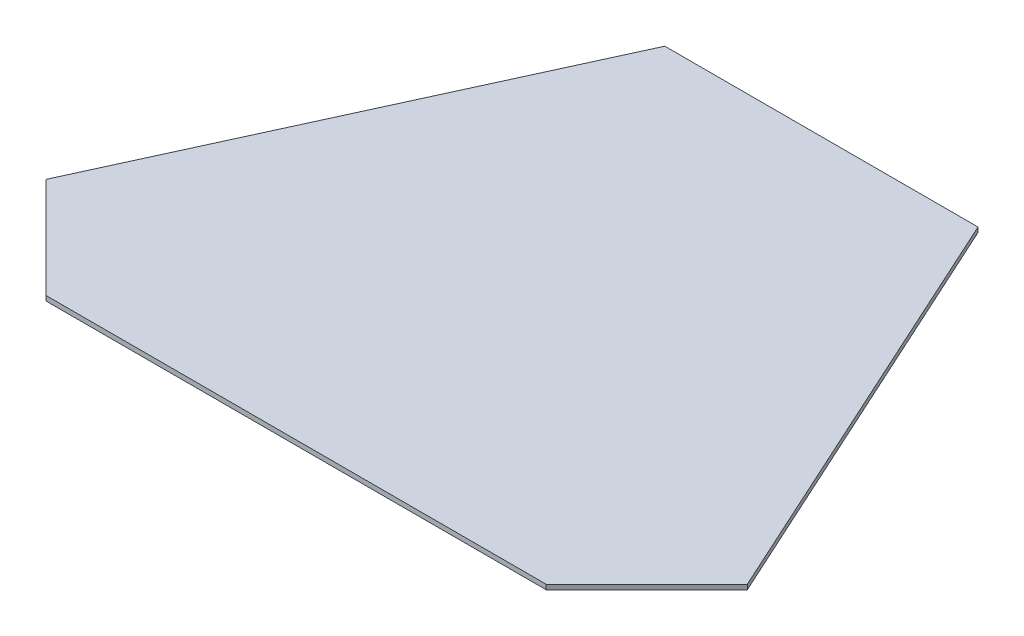
SolidWorks part; units mm, degrees
ref_plane "Front Plane" through (0, 0, 0) normal (0, 0, 1) x (1, 0, 0)
ref_plane "Top Plane" through (0, 0, 0) normal (0, 1, 0) x (1, 0, 0)
ref_plane "Right Plane" through (0, 0, 0) normal (1, 0, 0) x (0, 0, -1)
sketch "Sketch1" plane through (0, 0, 0) normal (0, 1, 0) x (1, 0, 0)
  line L1 (0, 0) -> (500, 0)
  line L2 (0, 0) -> (0, -500)
  line L3 (0, -500) -> (500, -500)
  line L4 (500, 0) -> (500, -500)
extrude "Boss-Extrude1" add sketch "Sketch1" along normal blind 2.9972
sketch "Sketch2" plane through (0, 2.9972, 0) normal (0, 1, 0) x (1, 0, 0)
  line L0 (315.9032, 0) -> (436.7476, -264.5165)
  line L1 (436.7476, -264.5165) -> (374.1336, -327.1305)
  line L2 (374.1336, -327.1305) -> (62.614, -327.1305)
  line L3 (62.614, -327.1305) -> (0, -264.5165)
  line L4 (0, -264.5165) -> (120.8445, 0)
  line L5 (120.8445, 0) -> (315.9032, 0)
extrude "Cut-Extrude1" cut sketch "Sketch2" against normal through all flip side to cut
